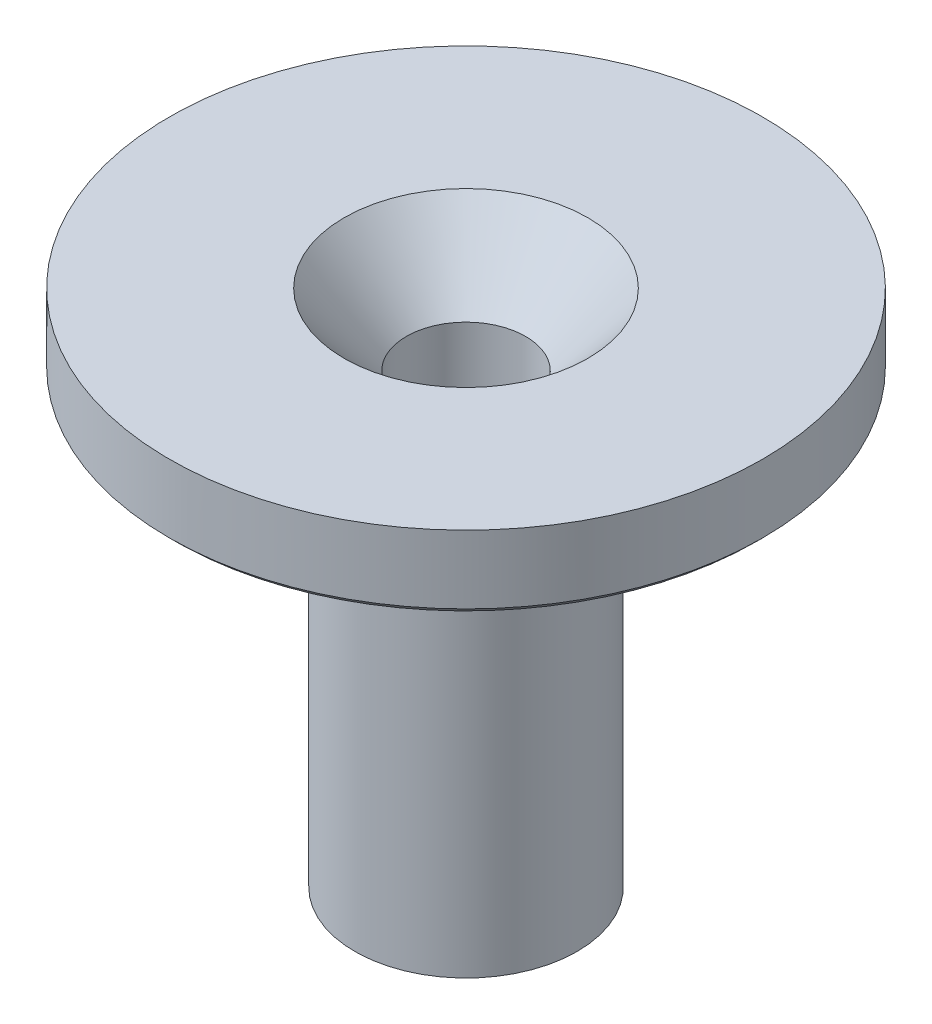
SolidWorks part; units mm, degrees
ref_plane "Front Plane" through (0, 0, 0) normal (0, 0, 1) x (1, 0, 0)
ref_plane "Top Plane" through (0, 0, 0) normal (0, 1, 0) x (1, 0, 0)
ref_plane "Right Plane" through (0, 0, 0) normal (1, 0, 0) x (0, 0, -1)
sketch "Sketch2" plane through (0, 0, 0) normal (0, 0, 1) x (1, 0, 0)
  line L0 (0, 10.1405) -> (-12.7, 10.1405)
  line L1 (0, -55) -> (0, 55) construction
  line L2 (-12.7, 10.1405) -> (-12.7, 6.9655)
  line L3 (-12.7, 6.9655) -> (-4.7625, 6.9655)
  line L4 (-4.7625, 6.9655) -> (-4.7625, -12.0845)
  line L5 (-4.7625, -12.0845) -> (0, -12.0845)
  line L6 (0, -12.0845) -> (0, 10.1405) construction
  line L7 (0, 10.1405) -> (0, -12.0845)
  point P8 (-2.3812, -12.0845)
  dimension "D1" = 19.05
  dimension "D2" = 12.7
  dimension "D3" = 4.7625
  dimension "D4" = 3.175
revolve "Revolve1" add sketch "Sketch2" angle 360 about L6
hole_wizard "CSK for #10 Flat Head Socket Cap Screw1" positions "Sketch3" profile "Sketch4" countersink size "#10" standard "ANSI Inch" end condition through all
sketch "Sketch3" plane through (0, 10.1405, 0) normal (0, 1, 0) x (1, 0, 0)
  point P0 (0, 0)
sketch "Sketch4" plane through (0, 10.1405, 0) normal (1, 0, 0) x (0, 0, 1)
  line L0 (0, 0) -> (0, 22.225)
  line L1 (0, 22.225) -> (2.5527, 22.225)
  line L2 (2.5527, 22.225) -> (2.5527, 3.068)
  line L3 (2.5527, 3.068) -> (5.2197, 0)
  line L5 (5.2197, 0) -> (0, 0)
  line L6 (-2.5527, 3.068) -> (-5.2197, 0) construction
  line L11 (0, -6.35) -> (0, 107.95) construction
  dimension "Thru Hole Dia." = 5.1054
  dimension "Thru Hole Depth" = 22.225
  dimension "Near C'Sink Dia." = 10.4394
  dimension "Near C'Sink Angle" = 82
chamfer "Chamfer1" distance 0.254 angle 45 1 edges at (12.7, 6.9655, 0)
